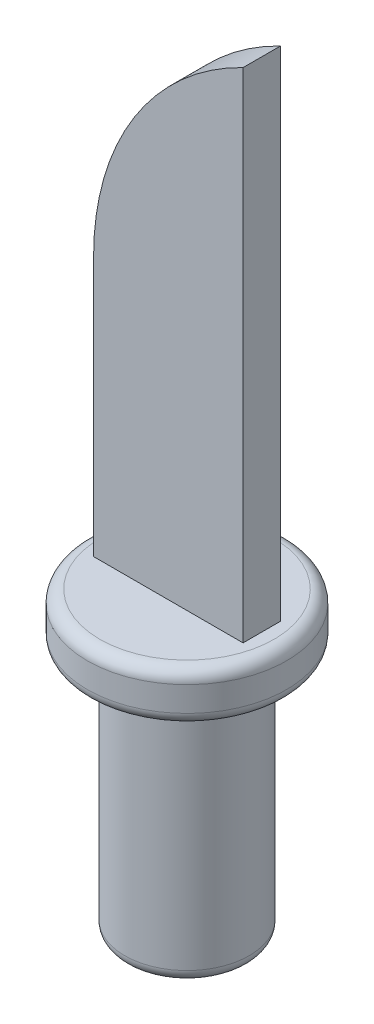
SolidWorks part; units mm, degrees
ref_plane "前视基准面" through (0, 0, 0) normal (0, 0, 1) x (1, 0, 0)
ref_plane "上视基准面" through (0, 0, 0) normal (0, 1, 0) x (1, 0, 0)
ref_plane "右视基准面" through (0, 0, 0) normal (1, 0, 0) x (0, 0, -1)
sketch "草图1" plane through (0, 0, 0) normal (0, 0, 1) x (1, 0, 0)
  line L0 (0, 0) -> (0, 100)
  dimension "D1" = 100
sweep "扫描1" add path "草图1" circular profile diameter 50 parameters "D3"=50
sketch "草图9" plane through (0, 100, 0) normal (0, 1, 0) x (1, 0, 0)
  circle A0 centre (0, 0) radius 40
  dimension "D1" = 80
extrude "凸台-拉伸2" add sketch "草图9" along normal blind 20 contours A0
fillet "圆角1" radius 5 3 edges at (0, 0, 25) (0, 120, 40) (0, 100, 40)
sketch "草图11" plane through (0, 120, 0) normal (0, 1, 0) x (1, 0, 0)
  line L1 (30, -7.5) -> (-30, -7.5)
  line L2 (30, -7.5) -> (30, 7.5)
  line L3 (30, 7.5) -> (-30, 7.5)
  line L4 (-30, -7.5) -> (-30, 7.5)
  line L5 (30, -7.5) -> (-30, 7.5) construction
  line L6 (30, 7.5) -> (-30, -7.5) construction
  point P0 (0, 0)
  dimension "D1" = 15
  dimension "D2" = 60
extrude "凸台-拉伸3" add sketch "草图11" along normal blind 200
sketch "草图12" plane through (0, 0, 7.5) normal (0, 0, 1) x (1, 0, 0)
  line L7 (-30, 320) -> (-30, 120) construction
  line L12 (-30, 224.2616) -> (-30, 320)
  line L13 (-30, 320) -> (30, 320)
  arc A3 (30, 320) -> (-30, 224.2616) centre (76.382, 224.2616) ccw
extrude "切除-拉伸1" cut sketch "草图12" against normal through all
scale "缩放比例1" bodies to scale 105 scale about centroid uniform scaling yes scale factor 0.05
